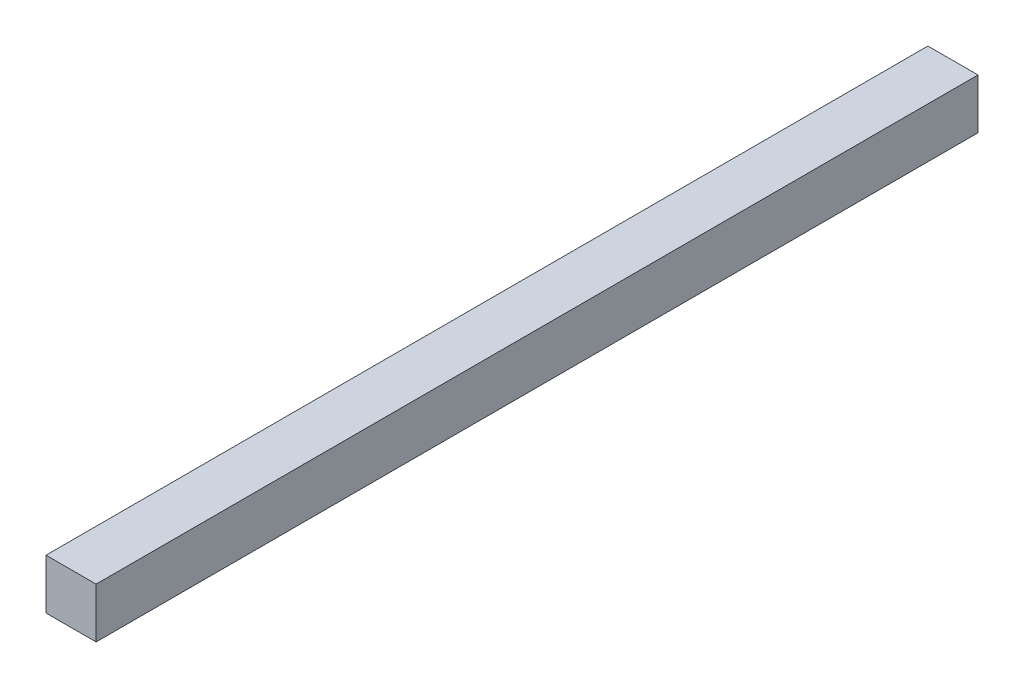
SolidWorks part; units mm, degrees
ref_plane "Plano frontal" through (0, 0, 0) normal (0, 0, 1) x (1, 0, 0)
ref_plane "Plano superior" through (0, 0, 0) normal (0, 1, 0) x (1, 0, 0)
ref_plane "Plano direito" through (0, 0, 0) normal (1, 0, 0) x (0, 0, -1)
sketch "Esboço1" plane through (0, 0, 0) normal (0, 0, 1) x (1, 0, 0)
  line L1 (0, 0) -> (-0.5, 0)
  line L2 (0, 0) -> (0, 0.5)
  line L3 (0, 0.5) -> (-0.5, 0.5)
  line L4 (-0.5, 0) -> (-0.5, 0.5)
  dimension "D1" = 0.5
  dimension "D2" = 0.5
extrude "Ressalto-extrusão1" add sketch "Esboço1" along normal blind 8.8
